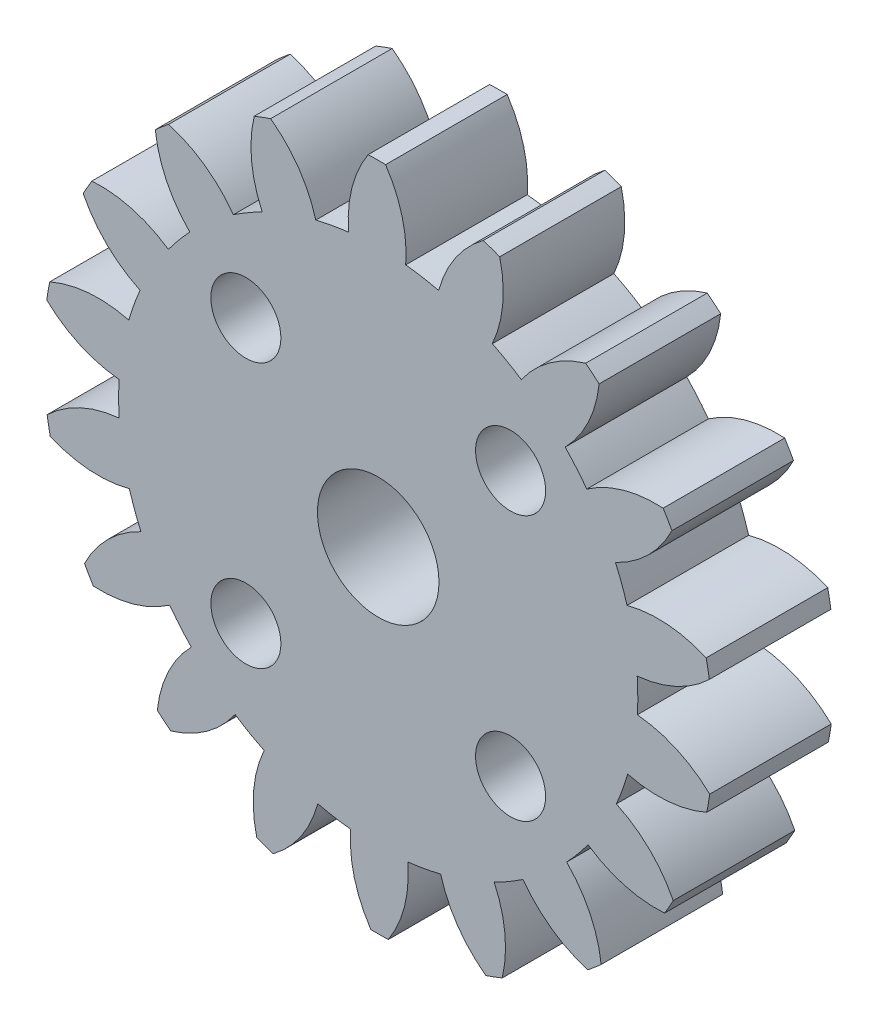
SolidWorks part; units mm, degrees
material "ABS"
ref_plane "Plan de face" through (0, 0, 0) normal (0, 0, 1) x (1, 0, 0)
ref_plane "Plan de dessus" through (0, 0, 0) normal (0, 1, 0) x (1, 0, 0)
ref_plane "Plan de droite" through (0, 0, 0) normal (1, 0, 0) x (0, 0, -1)
sketch "Esquisse1" plane through (0, 0, 0) normal (0, 0, 1) x (1, 0, 0)
  arc A144 (12.3963, 5.4996) -> (15.3448, 8.4134) centre (9.6887, 11.1881) ccw
  arc A145 (15.3448, 8.4134) -> (14.8846, 9.2031) centre (0, 0) ccw
  arc A146 (14.8846, 9.2031) -> (10.8959, 8.0743) centre (14.5104, 2.9143) ccw
  arc A147 (10.8959, 8.0743) -> (9.7678, 9.4077) centre (0, 0) ccw
  arc A148 (9.7678, 9.4077) -> (11.5419, 13.1543) centre (5.2779, 13.8271) ccw
  arc A149 (11.5419, 13.1543) -> (10.8393, 13.739) centre (0, 0) ccw
  arc A150 (10.8393, 13.739) -> (7.4772, 11.3139) centre (12.6386, 7.7014) ccw
  arc A151 (7.4772, 11.3139) -> (5.9611, 12.1811) centre (0, 0) ccw
  arc A152 (5.9611, 12.1811) -> (6.3468, 16.3085) centre (0.2304, 14.7984) ccw
  arc A153 (6.3468, 16.3085) -> (5.4866, 16.6177) centre (0, 0) ccw
  arc A154 (5.4866, 16.6177) -> (3.1567, 13.189) centre (9.2424, 11.5596) ccw
  arc A155 (3.1567, 13.189) -> (1.4354, 13.4853) centre (0, 0) ccw
  arc A156 (1.4354, 13.4853) -> (0.3862, 17.4957) centre (-4.8448, 13.9847) ccw
  arc A157 (0.3862, 17.4957) -> (-0.5278, 17.492) centre (0, 0) ccw
  arc A158 (-0.5278, 17.492) -> (-1.5446, 13.4733) centre (4.7314, 14.0235) ccw
  arc A159 (-1.5446, 13.4733) -> (-3.2634, 13.163) centre (0, 0) ccw
  arc A160 (-3.2634, 13.163) -> (-5.621, 16.5727) centre (-9.3357, 11.4843) ccw
  arc A161 (-5.621, 16.5727) -> (-6.4786, 16.2566) centre (0, 0) ccw
  arc A162 (-6.4786, 16.2566) -> (-6.0595, 12.1324) centre (-0.3503, 14.796) ccw
  arc A163 (-6.0595, 12.1324) -> (-7.5686, 11.253) centre (0, 0) ccw
  arc A164 (-7.5686, 11.253) -> (-10.9502, 13.6507) centre (-12.7005, 7.5988) ccw
  arc A165 (-10.9502, 13.6507) -> (-11.648, 13.0604) centre (0, 0) ccw
  arc A166 (-11.648, 13.0604) -> (-9.8436, 9.3283) centre (-5.3897, 13.7839) ccw
  arc A167 (-9.8436, 9.3283) -> (-10.9609, 7.9857) centre (0, 0) ccw
  arc A168 (-10.9609, 7.9857) -> (-14.9587, 9.0823) centre (-14.5335, 2.7967) ccw
  arc A169 (-14.9587, 9.0823) -> (-15.4125, 8.2889) centre (0, 0) ccw
  arc A170 (-15.4125, 8.2889) -> (-12.4405, 5.399) centre (-9.779, 11.1092) ccw
  arc A171 (-12.4405, 5.399) -> (-13.0312, 3.7553) centre (0, 0) ccw
  arc A172 (-13.0312, 3.7553) -> (-17.1629, 3.4184) centre (-14.6136, -2.3428) ccw
  arc A173 (-17.1629, 3.4184) -> (-17.318, 2.5176) centre (0, 0) ccw
  arc A174 (-17.318, 2.5176) -> (-13.5368, 0.8185) centre (-12.9889, 7.0946) ccw
  arc A175 (-13.5368, 0.8185) -> (-13.5297, -0.9281) centre (0, 0) ccw
  arc A176 (-13.5297, -0.9281) -> (-17.297, -2.6578) centre (-12.931, -7.1996) ccw
  arc A177 (-17.297, -2.6578) -> (-17.1346, -3.5573) centre (0, 0) ccw
  arc A178 (-17.1346, -3.5573) -> (-13.0004, -3.8607) centre (-14.6321, 2.2243) ccw
  arc A179 (-13.0004, -3.8607) -> (-12.3963, -5.4996) centre (0, 0) ccw
  arc A180 (-12.3963, -5.4996) -> (-15.3448, -8.4134) centre (-9.6887, -11.1881) ccw
  arc A181 (-15.3448, -8.4134) -> (-14.8846, -9.2031) centre (0, 0) ccw
  arc A182 (-14.8846, -9.2031) -> (-10.8959, -8.0743) centre (-14.5104, -2.9143) ccw
  arc A183 (-10.8959, -8.0743) -> (-9.7678, -9.4077) centre (0, 0) ccw
  arc A184 (-9.7678, -9.4077) -> (-11.5419, -13.1543) centre (-5.2779, -13.8271) ccw
  arc A185 (-11.5419, -13.1543) -> (-10.8393, -13.739) centre (0, 0) ccw
  arc A186 (-10.8393, -13.739) -> (-7.4772, -11.3139) centre (-12.6386, -7.7014) ccw
  arc A187 (-7.4772, -11.3139) -> (-5.9611, -12.1811) centre (0, 0) ccw
  arc A188 (-5.9611, -12.1811) -> (-6.3468, -16.3085) centre (-0.2304, -14.7984) ccw
  arc A189 (-6.3468, -16.3085) -> (-5.4866, -16.6177) centre (0, 0) ccw
  arc A190 (-5.4866, -16.6177) -> (-3.1567, -13.189) centre (-9.2424, -11.5596) ccw
  arc A191 (-3.1567, -13.189) -> (-1.4354, -13.4853) centre (0, 0) ccw
  arc A192 (-1.4354, -13.4853) -> (-0.3862, -17.4957) centre (4.8448, -13.9847) ccw
  arc A193 (-0.3862, -17.4957) -> (0.5278, -17.492) centre (0, 0) ccw
  arc A194 (0.5278, -17.492) -> (1.5446, -13.4733) centre (-4.7314, -14.0235) ccw
  arc A195 (1.5446, -13.4733) -> (3.2634, -13.163) centre (0, 0) ccw
  arc A196 (3.2634, -13.163) -> (5.621, -16.5727) centre (9.3357, -11.4843) ccw
  arc A197 (5.621, -16.5727) -> (6.4786, -16.2566) centre (0, 0) ccw
  arc A198 (6.4786, -16.2566) -> (6.0595, -12.1324) centre (0.3503, -14.796) ccw
  arc A199 (6.0595, -12.1324) -> (7.5686, -11.253) centre (0, 0) ccw
  arc A200 (7.5686, -11.253) -> (10.9502, -13.6507) centre (12.7005, -7.5988) ccw
  arc A201 (10.9502, -13.6507) -> (11.648, -13.0604) centre (0, 0) ccw
  arc A202 (11.648, -13.0604) -> (9.8436, -9.3283) centre (5.3897, -13.7839) ccw
  arc A203 (9.8436, -9.3283) -> (10.9609, -7.9857) centre (0, 0) ccw
  arc A204 (10.9609, -7.9857) -> (14.9587, -9.0823) centre (14.5335, -2.7967) ccw
  arc A205 (14.9587, -9.0823) -> (15.4125, -8.2889) centre (0, 0) ccw
  arc A206 (15.4125, -8.2889) -> (12.4405, -5.399) centre (9.779, -11.1092) ccw
  arc A207 (12.4405, -5.399) -> (13.0312, -3.7553) centre (0, 0) ccw
  arc A208 (13.0312, -3.7553) -> (17.1629, -3.4184) centre (14.6136, 2.3428) ccw
  arc A209 (17.1629, -3.4184) -> (17.318, -2.5176) centre (0, 0) ccw
  arc A210 (17.318, -2.5176) -> (13.5368, -0.8185) centre (12.9889, -7.0946) ccw
  arc A211 (13.5368, -0.8185) -> (13.5297, 0.9281) centre (0, 0) ccw
  arc A212 (13.5297, 0.9281) -> (17.297, 2.6578) centre (12.931, 7.1996) ccw
  arc A213 (17.297, 2.6578) -> (17.1346, 3.5573) centre (0, 0) ccw
  arc A214 (17.1346, 3.5573) -> (13.0004, 3.8607) centre (14.6321, -2.2243) ccw
  arc A215 (13.0004, 3.8607) -> (12.3963, 5.4996) centre (0, 0) ccw
extrude "Boss.-Extru.1" add sketch "Esquisse1" along normal mid plane 6.35
sketch "Esquisse2" plane through (0, 0, 3.175) normal (0, 0, 1) x (1, 0, 0)
  circle A0 centre (0, 0) radius 3.175
  circle A1 centre (6.9148, 6.9148) radius 1.83
  arc A2 (6.9148, 5.1622) -> (7.5265, 8.5572) centre (6.9148, 6.9148) ccw construction
  circle A3 centre (6.9148, -6.9148) radius 1.83
  circle A4 centre (-6.9148, -6.9148) radius 1.83
  circle A5 centre (-6.9148, 6.9148) radius 1.83
  point P18 (0, 0)
  dimension "D1" = 3.66
  dimension "D2" = 6.35
  dimension "D3" = 4
extrude "Cut-Extrude1" cut sketch "Esquisse2" against normal through all
